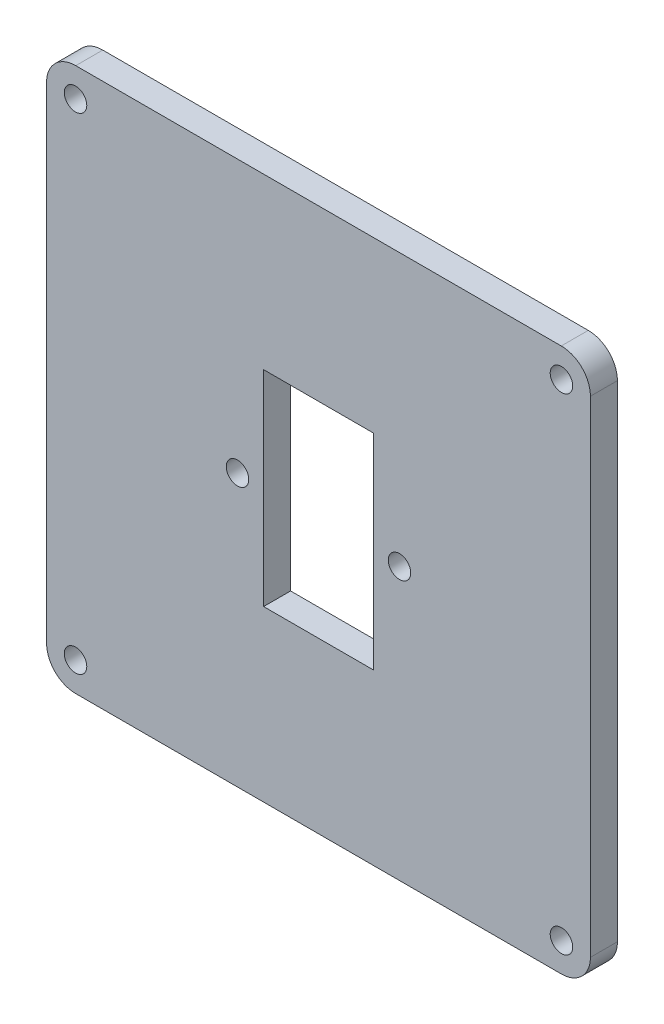
SolidWorks part; units mm, degrees
ref_plane "前基準面" through (0, 0, 0) normal (0, 0, 1) x (1, 0, 0)
ref_plane "上基準面" through (0, 0, 0) normal (0, 1, 0) x (1, 0, 0)
ref_plane "右基準面" through (0, 0, 0) normal (1, 0, 0) x (0, 0, -1)
sketch "草圖2" plane through (0, 0, 0) normal (0, 0, 1) x (1, 0, 0)
  line L0 (228.0408, 148.4236) -> (281.9938, 148.4236)
  line L1 (224.7994, 145.2061) -> (224.7994, 91.2061)
  line L2 (228.0426, 87.988) -> (281.992, 87.988)
  line L3 (285.2352, 91.2061) -> (285.2352, 145.2062)
  line L4 (248.9173, 106.8061) -> (261.1173, 106.8061) construction
  line L5 (261.1173, 106.8061) -> (261.1173, 129.6061) construction
  line L6 (261.1173, 129.6061) -> (248.9173, 129.6061) construction
  line L7 (248.9173, 129.6061) -> (248.9173, 106.8061) construction
  line L8 (248.9173, 106.8061) -> (261.1173, 106.8061)
  line L9 (261.1173, 106.8061) -> (261.1173, 129.6061)
  line L10 (261.1173, 129.6061) -> (248.9173, 129.6061)
  line L11 (248.9173, 129.6061) -> (248.9173, 106.8061)
  circle A0 centre (282.0173, 91.2058) radius 1.25 construction
  arc A1 (281.992, 87.988) -> (285.2352, 91.2061) centre (282.0173, 91.2058) ccw construction
  circle A2 centre (228.0173, 91.2058) radius 1.25 construction
  arc A3 (224.7994, 91.2061) -> (228.0426, 87.988) centre (228.0173, 91.2058) ccw construction
  circle A4 centre (282.0173, 145.2058) radius 1.25 construction
  arc A5 (285.2352, 145.2062) -> (281.9938, 148.4236) centre (282.0173, 145.2058) ccw construction
  circle A6 centre (246.0173, 118.2061) radius 1.25 construction
  circle A7 centre (264.0173, 118.2061) radius 1.25 construction
  circle A8 centre (228.0173, 145.2058) radius 1.25 construction
  arc A9 (228.0408, 148.4236) -> (224.7994, 145.2061) centre (228.0173, 145.2058) ccw construction
  circle A10 centre (282.0173, 91.2058) radius 1.25
  arc A11 (281.992, 87.988) -> (285.2352, 91.2061) centre (282.0173, 91.2058) ccw
  circle A12 centre (228.0173, 91.2058) radius 1.25
  arc A13 (224.7994, 91.2061) -> (228.0426, 87.988) centre (228.0173, 91.2058) ccw
  circle A14 centre (282.0173, 145.2058) radius 1.25
  arc A15 (285.2352, 145.2062) -> (281.9938, 148.4236) centre (282.0173, 145.2058) ccw
  circle A16 centre (246.0173, 118.2061) radius 1.25
  circle A17 centre (264.0173, 118.2061) radius 1.25
  circle A18 centre (228.0173, 145.2058) radius 1.25
  arc A19 (228.0408, 148.4236) -> (224.7994, 145.2061) centre (228.0173, 145.2058) ccw
  point P16 (282.0173, 145.2058)
extrude "填料-伸長1" add sketch "草圖2" along normal blind 3
